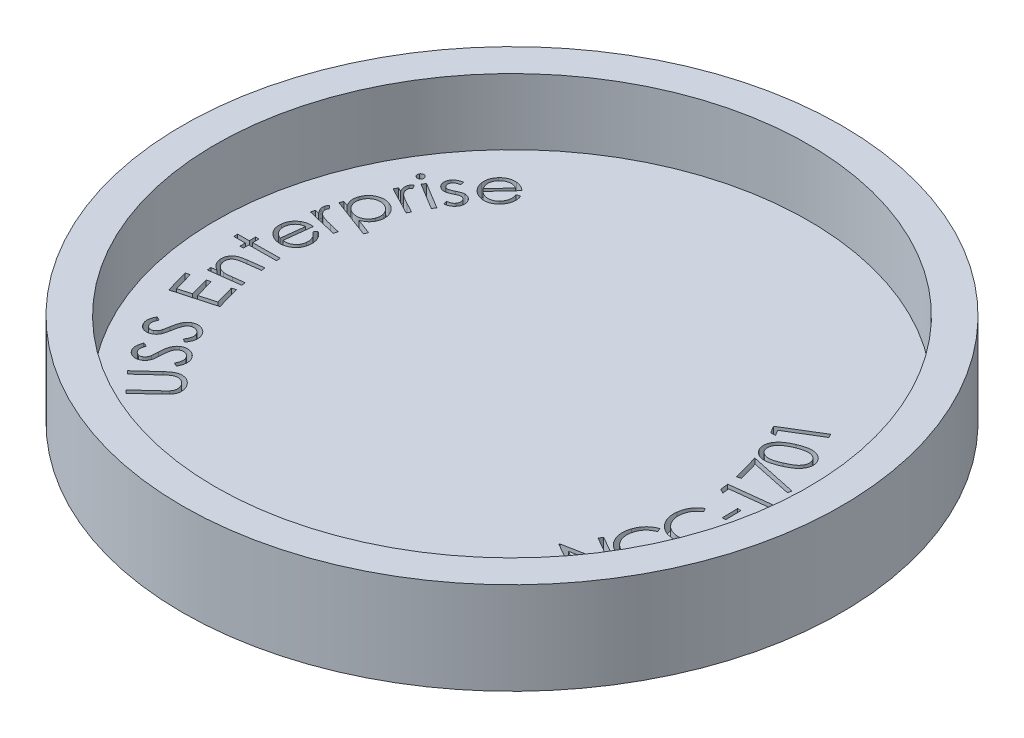
SolidWorks part; units mm, degrees
ref_plane "Front Plane" through (0, 0, 0) normal (0, 0, 1) x (1, 0, 0)
ref_plane "Top Plane" through (0, 0, 0) normal (0, 1, 0) x (1, 0, 0)
ref_plane "Right Plane" through (0, 0, 0) normal (1, 0, 0) x (0, 0, -1)
sketch "Sketch1" plane through (0, 0, 0) normal (0, 1, 0) x (1, 0, 0)
  circle A0 centre (0, 0) radius 50
extrude "Boss-Extrude1" add sketch "Sketch1" along normal blind 4
sketch "Sketch2" plane through (0, 4, 0) normal (0, 1, 0) x (1, 0, 0)
  circle A0 centre (0, 0) radius 50
  circle A1 centre (0, 0) radius 45
extrude "Boss-Extrude2" add sketch "Sketch2" along normal blind 10
sketch "Sketch8" plane through (0, 4, 0) normal (0, 1, 0) x (1, 0, 0)
  arc A0 (0, 35.148) -> (0, -35.148) centre (0, 0) cw
  arc A1 (0, -35.148) -> (0, 35.148) centre (0, 0) cw
sketch "Sketch9" plane through (0, 4, 0) normal (0, 1, 0) x (1, 0, 0)
  text T0 "NCC-1701" font "Century Gothic" height in points 24
  text T1 "USS Enterprise" font "Century Gothic" height in points 24
extrude "Cut-Extrude3" cut sketch "Sketch9" against normal blind 2
